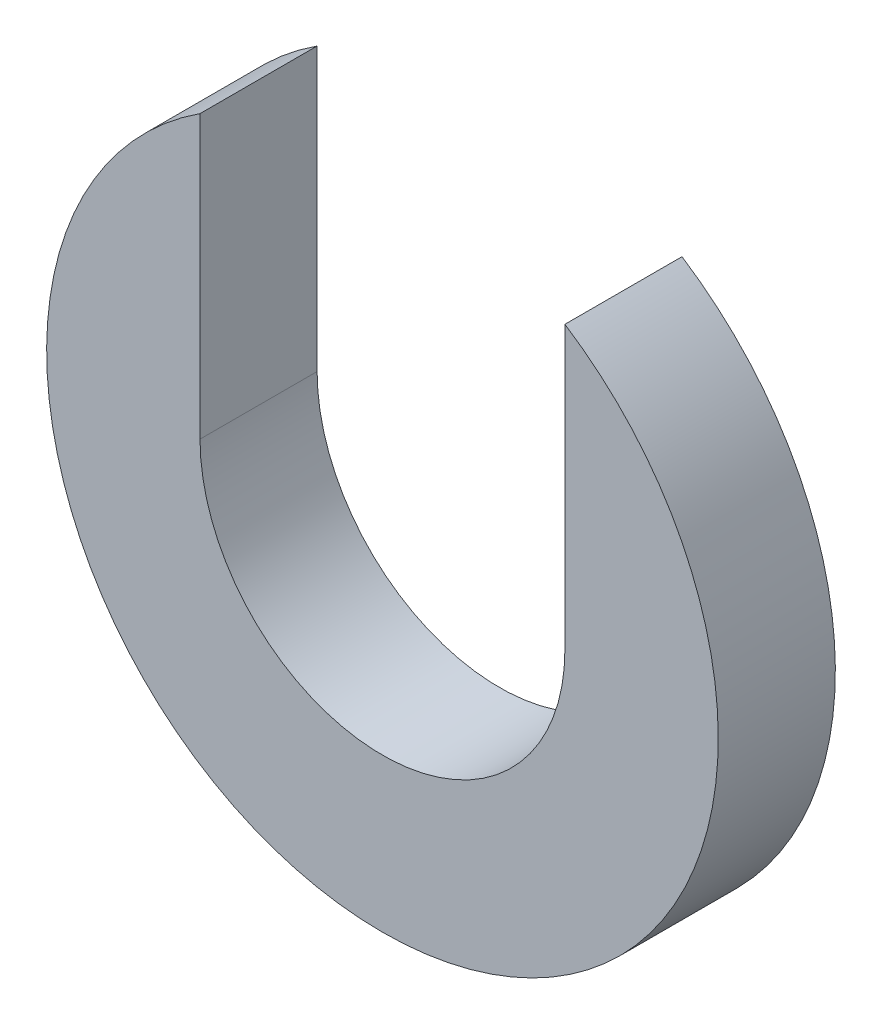
SolidWorks part; units mm, degrees
ref_plane "Front Plane" through (0, 0, 0) normal (0, 0, 1) x (1, 0, 0)
ref_plane "Top Plane" through (0, 0, 0) normal (0, 1, 0) x (1, 0, 0)
ref_plane "Right Plane" through (0, 0, 0) normal (1, 0, 0) x (0, 0, -1)
sketch "Sketch1" plane through (0, 0, 0) normal (0, 0, 1) x (1, 0, 0)
  circle A0 centre (0, 0) radius 9.12
extrude "Boss-Extrude1" add sketch "Sketch1" along normal blind 3.18
sketch "Sketch2" plane through (0, 0, 3.18) normal (0, 0, 1) x (1, 0, 0)
  line L0 (-4.955, 0) -> (-4.955, 7.6565)
  line L1 (4.955, 0) -> (4.955, 7.6565)
  arc A0 (-4.955, 0) -> (4.955, 0) centre (0, 0) ccw
  circle A1 centre (0, 0) radius 9.12 construction
  arc A2 (-4.955, 7.6565) -> (4.955, 7.6565) centre (0, 0) cw
  dimension "D1" = 9.91
extrude "Cut-Extrude1" cut sketch "Sketch2" against normal through all both and the other way through all
